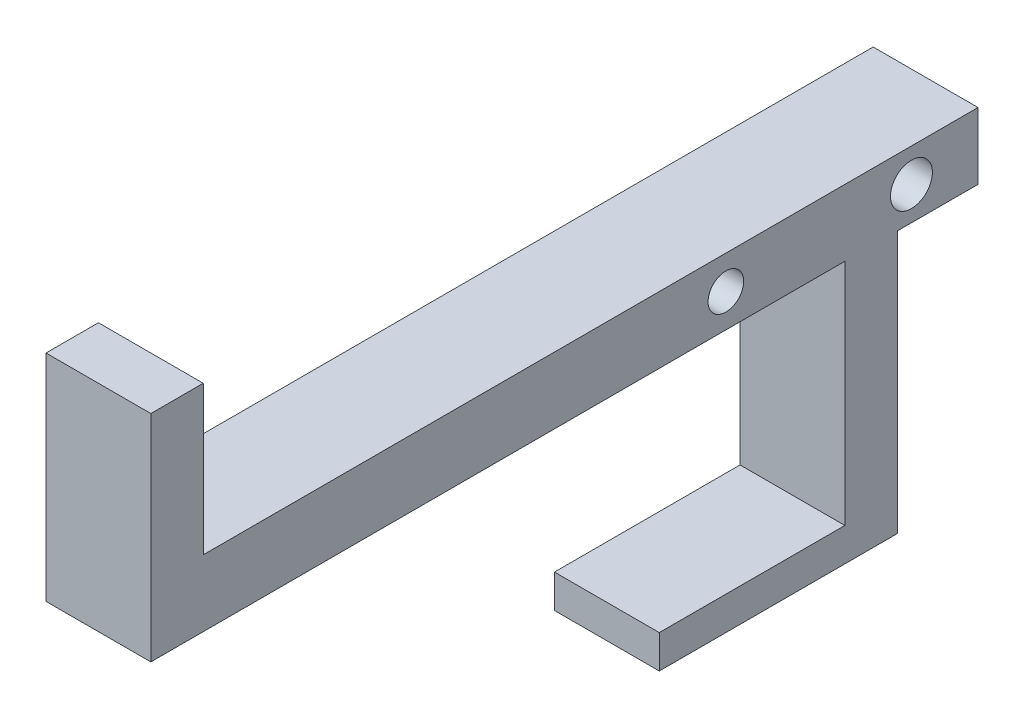
SolidWorks part; units mm, degrees
ref_plane "Front" through (0, 0, 0) normal (0, 0, 1) x (1, 0, 0)
ref_plane "Top" through (0, 0, 0) normal (0, 1, 0) x (1, 0, 0)
ref_plane "Right" through (0, 0, 0) normal (1, 0, 0) x (0, 0, -1)
sketch "Sketch1" plane through (0, 0, 0) normal (1, 0, 0) x (0, 0, -1)
  line L0 (0, 0) -> (0, 21.825)
  line L1 (0, 21.825) -> (-76.2, 21.825)
  line L2 (-76.2, 21.825) -> (-76.2, 28.175)
  line L3 (-76.2, 28.175) -> (17.7, 28.175)
  line L4 (17.7, 28.175) -> (17.7, 21.825)
  line L5 (17.7, 21.825) -> (5, 21.825)
  line L6 (5, 21.825) -> (5, -3.175)
  line L7 (5, -3.175) -> (-12.7, -3.175)
  line L8 (-12.7, -3.175) -> (-12.7, 0)
  line L9 (-12.7, 0) -> (0, 0)
  line L10 (-6.35, 28.175) -> (-6.35, 21.825)
  line L11 (-61.2, 28.175) -> (-61.2, 42.346)
  line L12 (-61.2, 42.346) -> (-56.2, 42.346)
  line L13 (-56.2, 42.346) -> (-56.2, 28.175)
  line L14 (-61.2, 28.175) -> (-61.2, 21.825)
  line L15 (-6.35, 25) -> (17.7, 25)
  line L16 (10, 21.825) -> (10, -3.175)
  line L17 (10, -3.175) -> (5, -3.175)
  line L18 (0, 21.825) -> (5, 21.825)
  line L19 (0, 0) -> (5, 0)
  line L20 (5, 0) -> (5, -3.175)
  circle A0 centre (-6.35, 25) radius 1.7
  circle A1 centre (11.35, 25) radius 2
  dimension "D2" = 6.35
  dimension "D11" = 6.35
  dimension "D1" = 12.7
  dimension "D3" = 12.7
  dimension "D4" = 76.2
  dimension "D5" = 6.35
  dimension "D6" = 25
  dimension "D7" = 3.175
  dimension "D8" = 15
  dimension "D9" = 5
  dimension "D10" = 5
  dimension "D12" = 5
extrude "Boss-Extrude1" add sketch "Sketch1" along normal blind 10 contours A0 L10 L3 L14 L1 | A1 L15 A0 L10 L1 L18 L5 L4 | A1 L15 L4 L3 L10 A0 | L17 L16 L5 L6 | L19 L9 L8 L7 L6 | L13 L12 L11 L3
